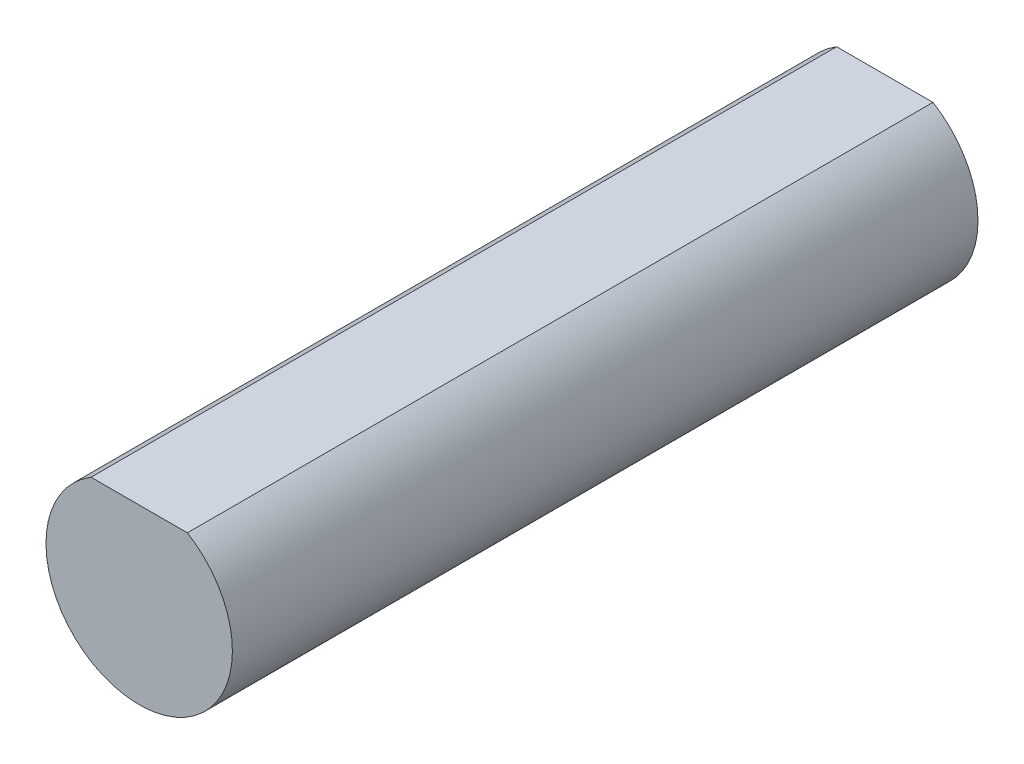
SolidWorks part; units mm, degrees
ref_plane "Front Plane" through (0, 0, 0) normal (0, 0, 1) x (1, 0, 0)
ref_plane "Top Plane" through (0, 0, 0) normal (0, 1, 0) x (1, 0, 0)
ref_plane "Right Plane" through (0, 0, 0) normal (1, 0, 0) x (0, 0, -1)
sketch "Sketch1" plane through (0, 0, 0) normal (0, 0, 1) x (1, 0, 0)
  circle A0 centre (0, 0) radius 3.175
  dimension "D1" = 6.35
extrude "Boss-Extrude1" add sketch "Sketch1" along normal blind 25.4
sketch "Sketch2" plane through (0, 0, 0) normal (0, 0, -1) x (-1, 0, 0)
  line L0 (-1.6414, 2.7178) -> (1.6414, 2.7178)
  circle A0 centre (0, 0) radius 3.175 construction
  arc A1 (-1.6414, 2.7178) -> (1.6414, 2.7178) centre (0, 0) cw
  dimension "D1" = 2.7178
extrude "Cut-Extrude1" cut sketch "Sketch2" against normal through all
